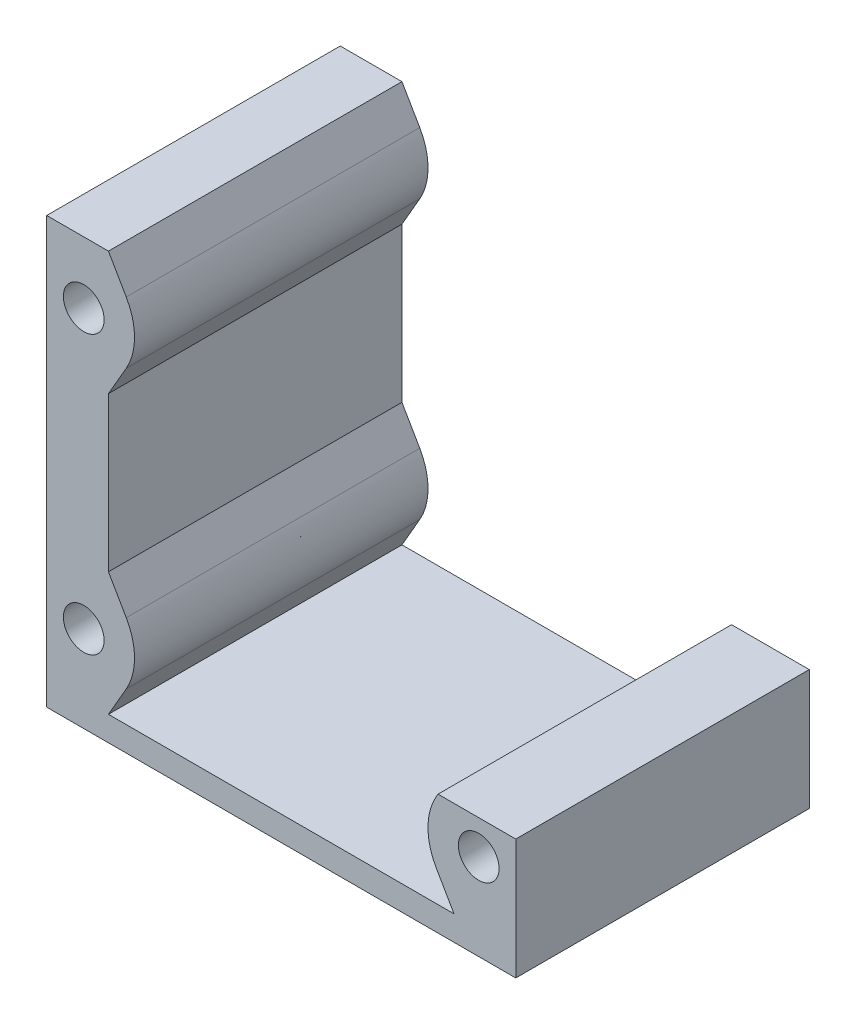
SolidWorks part; units mm, degrees
ref_plane "Ebene vorne" through (0, 0, 0) normal (0, 0, 1) x (1, 0, 0)
ref_plane "Ebene oben" through (0, 0, 0) normal (0, 1, 0) x (1, 0, 0)
ref_plane "Ebene rechts" through (0, 0, 0) normal (1, 0, 0) x (0, 0, -1)
sketch "Skizze1" plane through (-38, 0, 0) normal (-1, 0, 0) x (0, 0, 1)
  line L1 (70.0574, -4) -> (22.5, -4)
  line L2 (70.0574, -4) -> (70.0574, 0)
  line L3 (70.0574, 0) -> (22.5, 0)
  line L4 (22.5, -4) -> (22.5, 0)
extrude "Aufsatz-Linear austragen1" add sketch "Skizze1" against normal up to surface (76 mm away)
sketch "Skizze2" plane through (0, 0, 22.5) normal (0, 0, 1) x (1, 0, 0)
  line L24 (-38, 65) -> (-38, 0)
  line L25 (-38, 0) -> (-28, 0)
  line L26 (-28, 0) -> (-22.2265, 10)
  line L27 (-22.2265, 10) -> (-28, 20)
  line L28 (-28, 20) -> (-28, 45)
  line L29 (-28, 45) -> (-22.2265, 55)
  line L30 (-22.2265, 55) -> (-28, 65)
  line L31 (-28, 65) -> (-38, 65)
  line L32 (-38, 65) -> (-38, 0)
  line L33 (-38, 0) -> (-28, 0)
  line L34 (-28, 0) -> (-22.2265, 10)
  line L35 (-22.2265, 10) -> (-28, 20)
  line L36 (-28, 20) -> (-28, 45)
  line L37 (-28, 45) -> (-22.2265, 55)
  line L38 (-22.2265, 55) -> (-28, 65)
  line L39 (-28, 65) -> (-38, 65)
  line L128 (0, 0) -> (0, 65) construction
  line L129 (28, 65) -> (38, 65)
  line L130 (22.2265, 55) -> (28, 65)
  line L131 (28, 45) -> (22.2265, 55)
  line L132 (28, 20) -> (28, 45)
  line L133 (22.2265, 10) -> (28, 20)
  line L134 (28, 0) -> (22.2265, 10)
  line L135 (38, 0) -> (28, 0)
  line L136 (38, 65) -> (38, 0)
  dimension "D2" = 0
extrude "Aufsatz-Linear austragen2" add sketch "Skizze2" along normal up to surface (47.5574 mm away)
fillet "Verrundung1" radius 10 4 edges at (-22.2265, 10, 46.2787) (-22.2265, 55, 46.2787) (22.2265, 10, 46.2787) (22.2265, 55, 46.2787)
sketch "Skizze3" plane through (0, 0, 22.5) normal (0, 0, -1) x (-1, 0, 0)
  circle A1 centre (32, 10) radius 3.3
  circle A2 centre (32, 10) radius 3.3
  circle A3 centre (32, 55) radius 3.3
  circle A4 centre (32, 55) radius 3.3
  circle A5 centre (-32, 55) radius 3.3
  circle A6 centre (-32, 55) radius 3.3
  circle A7 centre (-32, 10) radius 3.3
  circle A8 centre (-32, 10) radius 3.3
  dimension "D1" = 0
  dimension "D2" = 0
  dimension "D3" = 0
  dimension "D4" = 0
extrude "Schnitt-Linear austragen1" cut sketch "Skizze3" against normal up to surface (47.5574 mm away) up to face at (0, 32.1, 70.0574)
sketch "Skizze4" plane through (38, 0, 0) normal (-1, 0, 0) x (0, 0, 1)
  line L0 (46.2787, -4) -> (46.2787, 65) construction
  line L1 (22.5, 30.5) -> (70.0574, 30.5)
  line L2 (22.5, 30.5) -> (22.5, 15.5)
  line L3 (22.5, 15.5) -> (70.0574, 15.5)
  line L4 (70.0574, 30.5) -> (70.0574, 15.5)
  line L5 (22.5, -4) -> (70.0574, -4) construction
  line L6 (70.0574, 65) -> (22.5, 65) construction
  line L7 (22.5, 30.5) -> (70.0574, 30.5) construction
  line L8 (22.5, 65) -> (22.5, -4) construction
  line L9 (70.0574, -4) -> (70.0574, 65) construction
  point P10 (46.2787, 30.5)
  dimension "D1" = 15
extrude "Schnitt-Linear austragen2" cut sketch "Skizze4" along normal blind 30
sketch "Skizze5" plane through (38, 0, 0) normal (1, 0, 0) x (0, 0, -1)
  line L1 (-70.0574, 65) -> (-22.5, 65)
  line L2 (-70.0574, 65) -> (-70.0574, 30.5)
  line L3 (-70.0574, 30.5) -> (-22.5, 30.5)
  line L4 (-22.5, 65) -> (-22.5, 30.5)
extrude "temporär" cut sketch "Skizze5" against normal blind 20
